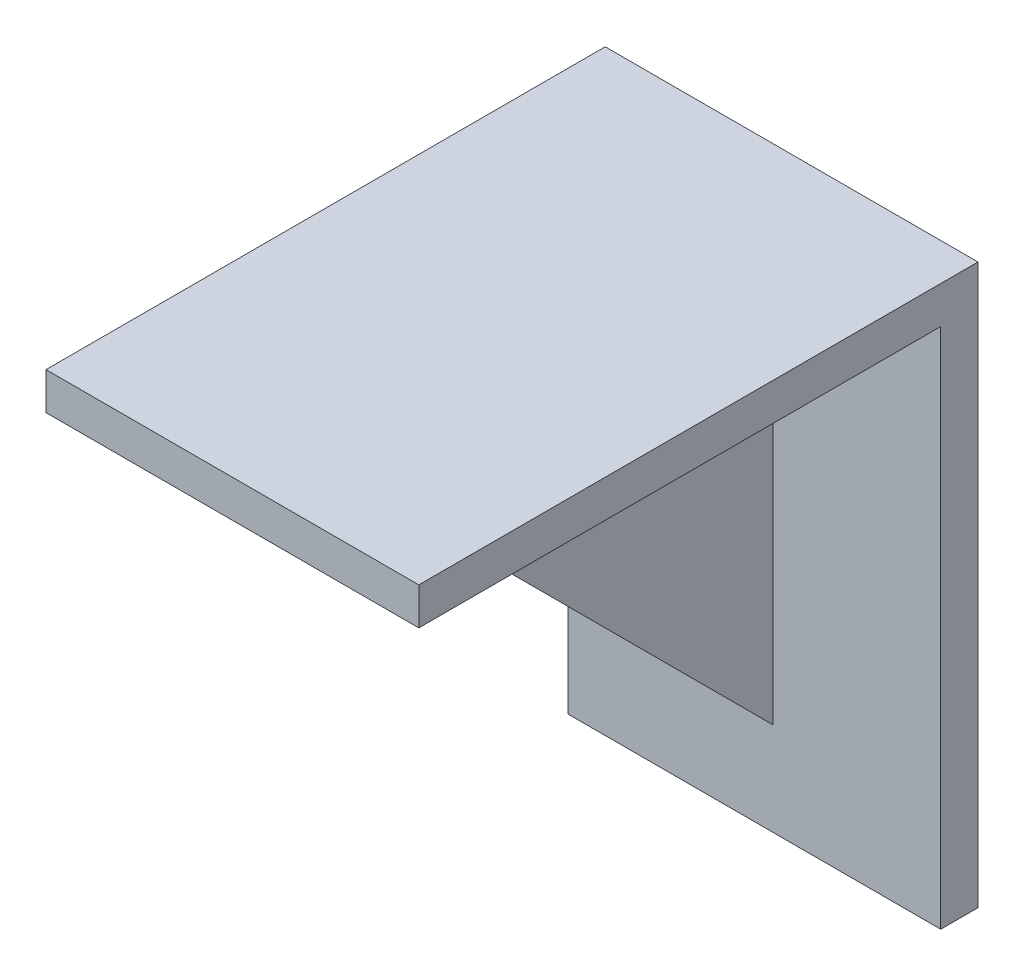
SolidWorks part; units mm, degrees
material "Ti-6Al-4VSolution treated and aged (SS)"
ref_plane "Front Plane" through (0, 0, 0) normal (0, 0, 1) x (1, 0, 0)
ref_plane "Top Plane" through (0, 0, 0) normal (0, 1, 0) x (1, 0, 0)
ref_plane "Right Plane" through (0, 0, 0) normal (1, 0, 0) x (0, 0, -1)
sketch "Sketch2" plane through (0, 0, 0) normal (0, 1, 0) x (1, 0, 0)
  line L0 (0, 0) -> (100, 0)
  line L1 (100, 0) -> (100, 150)
  line L2 (100, 150) -> (0, 150)
  line L3 (0, 150) -> (0, 0)
  dimension "D1" = 100
  dimension "D2" = 150
extrude "Boss-Extrude1" add sketch "Sketch2" along normal blind 150
sketch "Sketch3" plane through (0, 0, 0) normal (-1, 0, 0) x (0, 0, 1)
  line L0 (-25, 140) -> (0, 140)
  line L1 (-25, 140) -> (-140, 25)
  line L2 (-140, 25) -> (-140, 0)
  line L3 (-150, 0) -> (-140, 0)
  line L4 (-150, 0) -> (0, 0)
  line L5 (0, 0) -> (0, 150)
  line L6 (0, 150) -> (-150, 150)
  line L7 (-150, 150) -> (-150, 0)
  line L8 (-150, 0) -> (0, 0)
  line L9 (0, 0) -> (0, 140)
  line L13 (0, 140) -> (0, 150)
  line L14 (-150, 150) -> (-150, 0) construction
  line M9 (-150, 0) -> (0, 0)
  line M10 (0, 0) -> (0, 150)
  dimension "D2" = 25
  dimension "D3" = 10
  dimension "D1" = 0
extrude "Cut-Extrude1" cut sketch "Sketch3" against normal through all contours L1 L2 L0 M9 M10
sketch "Sketch4" plane through (0, 0, 0) normal (-1, 0, 0) x (0, 0, 1)
  line L0 (-25, 140) -> (-174.1283, 140)
  line L1 (-174.1283, 140) -> (-140, 174.1283)
  line L2 (-140, 174.1283) -> (-140, 25)
  line L3 (-25, 140) -> (-140, 25) construction
  line M12 (-140, 25) -> (-25, 140)
extrude "Cut-Extrude2" cut sketch "Sketch4" against normal blind 45 contours L1 L2 L0 M12
ref_plane "Plane1" through (50, 0, 0) normal (1, 0, 0) x (0, 0, -1)
mirror "Mirror1" about plane through (50, 0, 0) normal (1, 0, 0) of "Cut-Extrude2"
